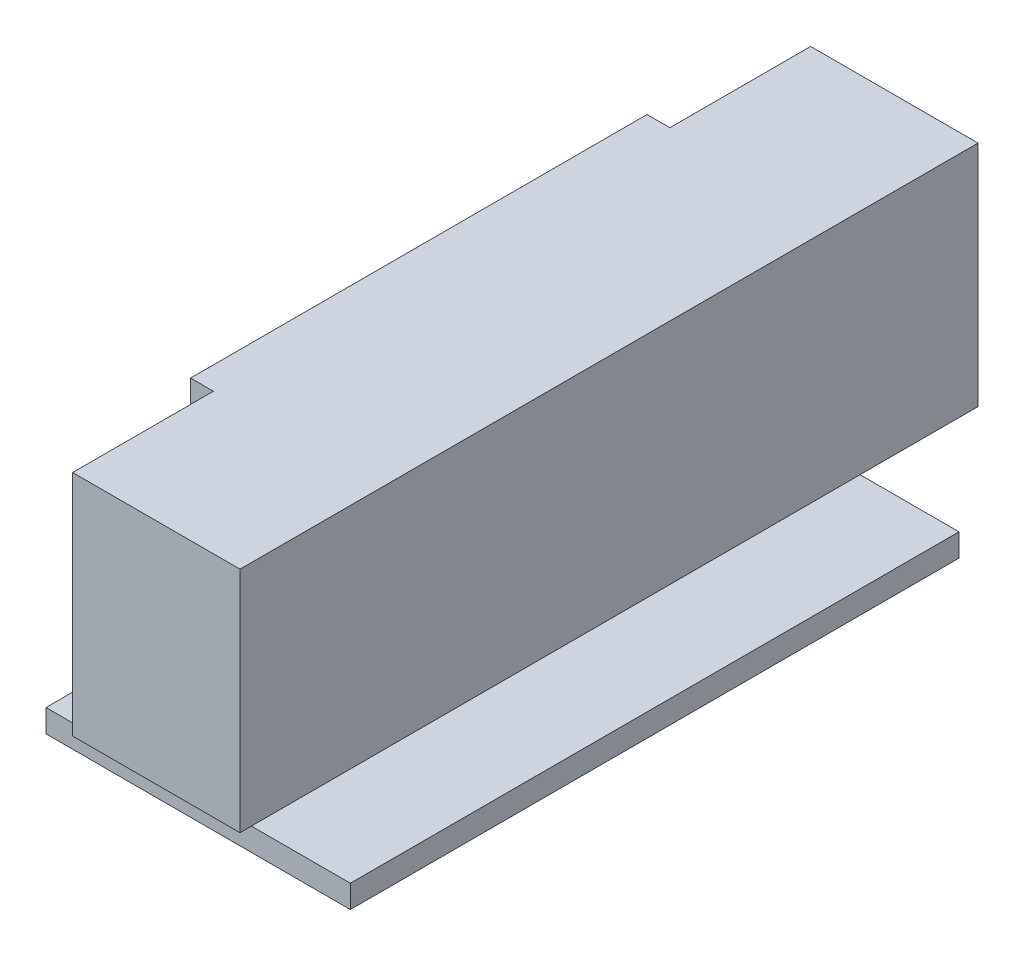
SolidWorks part; units mm, degrees
ref_plane "Front Plane" through (0, 0, 0) normal (0, 0, 1) x (1, 0, 0)
ref_plane "Top Plane" through (0, 0, 0) normal (0, 1, 0) x (1, 0, 0)
ref_plane "Right Plane" through (0, 0, 0) normal (1, 0, 0) x (0, 0, -1)
sketch "SK_P01_Bracketbase" plane through (0, 0, 0) normal (0, 1, 0) x (1, 0, 0)
  line L0 (-20, -40) -> (20, -40)
  line L1 (20, -40) -> (20, 40)
  line L2 (20, 40) -> (-20, 40)
  line L3 (-20, 40) -> (-20, -40)
extrude "P01_Bracketbase" add sketch "SK_P01_Bracketbase" along normal blind 3
sketch "SK_P02_Bracketupright" plane through (0, 0, 0) normal (0, 1, 0) x (1, 0, 0)
  line L0 (-11, -30) -> (-8, -30)
  line L1 (-8, -30) -> (-8, 30)
  line L2 (-8, 30) -> (-11, 30)
  line L3 (-11, 30) -> (-11, -30)
extrude "P02_Bracketupright" add sketch "SK_P02_Bracketupright" along normal blind 40
sketch "SK_P03_Camera" plane through (0, 0, 0) normal (0, 1, 0) x (1, 0, 0)
  line L0 (-8, -48.5) -> (14, -48.5)
  line L1 (14, -48.5) -> (14, 48.5)
  line L2 (14, 48.5) -> (-8, 48.5)
  line L3 (-8, 48.5) -> (-8, -48.5)
extrude "P03_Camera" add sketch "SK_P03_Camera" along normal blind 30 from offset 10
